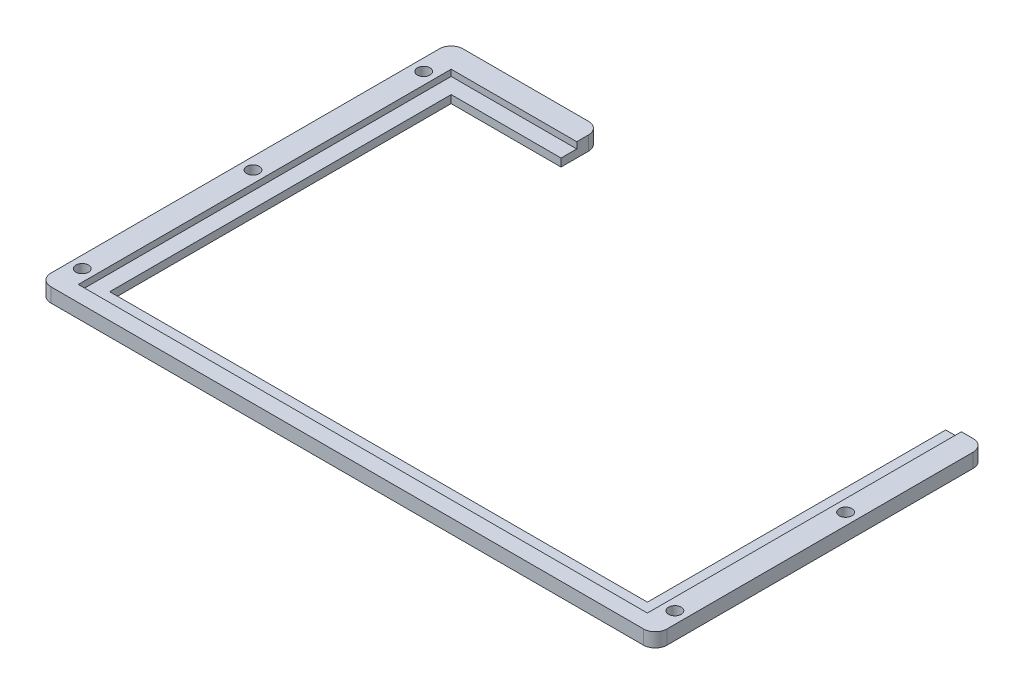
SolidWorks part; units mm, degrees
material "ABS"
ref_plane "Front Plane" through (0, 0, 0) normal (0, 0, 1) x (1, 0, 0)
ref_plane "Top Plane" through (0, 0, 0) normal (0, 1, 0) x (1, 0, 0)
ref_plane "Right Plane" through (0, 0, 0) normal (1, 0, 0) x (0, 0, -1)
sketch "Sketch1" plane through (0, 0, 0) normal (0, 1, 0) x (1, 0, 0)
  line L0 (-64.2938, 80.1687) -> (-64.2938, 69.0562)
  line L1 (115.0937, -75.4062) -> (-115.0938, -75.4063) construction
  line L2 (115.0937, -75.4062) -> (115.0937, 75.4062) construction
  line L3 (115.0937, 75.4062) -> (-115.0938, 75.4062) construction
  line L4 (-115.0938, -75.4063) -> (-115.0938, 75.4062) construction
  line L5 (115.0937, -75.4062) -> (-115.0938, 75.4062) construction
  line L6 (115.0937, 75.4062) -> (-115.0938, -75.4063) construction
  line L7 (-64.2938, 69.0562) -> (-108.7438, 69.0562)
  line L8 (-108.7438, 69.0562) -> (-108.7438, -69.0563)
  line L9 (-108.7438, -69.0563) -> (108.7437, -69.0563)
  line L10 (108.7437, -69.0563) -> (108.7437, 51.5938)
  line L11 (108.7437, 51.5938) -> (119.8562, 51.5938)
  line L12 (124.6187, 46.8313) -> (124.6187, -76.9937)
  line L13 (119.8562, -81.7562) -> (-119.8563, -81.7563)
  line L14 (-124.6188, -76.9938) -> (-124.6188, 80.1687)
  line L15 (-119.8563, 84.9312) -> (-69.0563, 84.9312)
  arc A0 (-64.2938, 80.1687) -> (-69.0563, 84.9312) centre (-69.0563, 80.1687) ccw
  arc A1 (-124.6188, 80.1687) -> (-119.8563, 84.9312) centre (-119.8563, 80.1687) cw
  arc A2 (119.8562, 51.5938) -> (124.6187, 46.8313) centre (119.8562, 46.8313) cw
  arc A3 (124.6187, -76.9937) -> (119.8562, -81.7562) centre (119.8562, -76.9937) cw
  arc A4 (-119.8563, -81.7563) -> (-124.6188, -76.9938) centre (-119.8563, -76.9938) cw
  point P0 (0, 0)
  dimension "D13" = 4.7625
  dimension "D1" = 230.1875
  dimension "D2" = 150.8125
  dimension "D3" = 6.35
  dimension "D4" = 6.35
  dimension "D5" = 6.35
  dimension "D6" = 9.525
  dimension "D7" = 6.35
  dimension "D8" = 9.525
  dimension "D9" = 127
  dimension "D10" = 50.8
  dimension "D11" = 6.35
  dimension "D12" = 9.525
extrude "Boss-Extrude1" add sketch "Sketch1" along normal blind 3.175
sketch "Sketch2" plane through (0, 3.175, 0) normal (0, 1, 0) x (1, 0, 0)
  line L0 (-64.2937, 80.1688) -> (-64.2937, 75.4063)
  line L1 (115.0938, -75.4062) -> (-115.0937, -75.4062) construction
  line L2 (115.0938, -75.4062) -> (115.0938, 75.4063) construction
  line L3 (115.0938, 75.4063) -> (-115.0937, 75.4063) construction
  line L4 (-115.0937, -75.4062) -> (-115.0937, 75.4063) construction
  line L5 (115.0938, -75.4062) -> (-115.0937, 75.4063) construction
  line L6 (115.0938, 75.4063) -> (-115.0937, -75.4062) construction
  line L7 (-64.2937, 75.4063) -> (-115.0937, 75.4063)
  line L8 (-115.0937, 75.4063) -> (-115.0937, -75.4062)
  line L9 (-115.0937, -75.4062) -> (115.0938, -75.4062)
  line L10 (115.0938, -75.4062) -> (115.0938, 51.5938)
  line L11 (115.0938, 51.5938) -> (119.8563, 51.5938)
  line L12 (124.6188, 46.8313) -> (124.6188, -76.9937)
  line L13 (119.8563, -81.7562) -> (-119.8562, -81.7562)
  line L14 (-124.6187, -76.9937) -> (-124.6187, 80.1688)
  line L15 (-119.8562, 84.9313) -> (-69.0562, 84.9313)
  arc A0 (-64.2937, 80.1688) -> (-69.0562, 84.9313) centre (-69.0562, 80.1688) ccw
  arc A1 (-124.6187, 80.1688) -> (-119.8562, 84.9313) centre (-119.8562, 80.1688) cw
  arc A2 (119.8563, 51.5938) -> (124.6188, 46.8313) centre (119.8563, 46.8313) cw
  arc A3 (124.6188, -76.9937) -> (119.8563, -81.7562) centre (119.8563, -76.9937) cw
  arc A4 (-119.8562, -81.7562) -> (-124.6187, -76.9937) centre (-119.8562, -76.9937) cw
  point P0 (0, 0)
  dimension "D13" = 4.7625
  dimension "D1" = 230.1875
  dimension "D2" = 150.8125
  dimension "D6" = 9.525
  dimension "D7" = 6.35
  dimension "D8" = 9.525
  dimension "D9" = 127
  dimension "D10" = 50.8
  dimension "D12" = 9.525
extrude "Boss-Extrude2" add sketch "Sketch2" along normal blind 2.54
sketch "Sketch3" plane through (0, 5.715, -5.715) normal (0, 1, 0) x (-1, 0, 0)
  line L0 (119.8563, 82.7088) -> (119.8563, -74.4537) construction
  line L1 (-119.8562, 82.7087) -> (-119.8562, -41.1163) construction
  line L2 (119.8562, 5.715) -> (-119.8562, 5.715) construction
  line L3 (-108.7437, 74.7713) -> (108.7438, 74.7713) construction
  line L5 (108.7438, -63.3412) -> (64.2938, -63.3412) construction
  circle A0 centre (119.8563, -63.3412) radius 2.5527
  circle A1 centre (119.8562, 74.7713) radius 2.5527
  circle A2 centre (119.8562, 5.715) radius 2.5527
  circle A3 centre (-119.8562, 74.7713) radius 2.5527
  circle A4 centre (-119.8562, 5.715) radius 2.5527
  dimension "D1" = 5.1054
extrude "Cut-Extrude1" cut sketch "Sketch3" against normal through all
